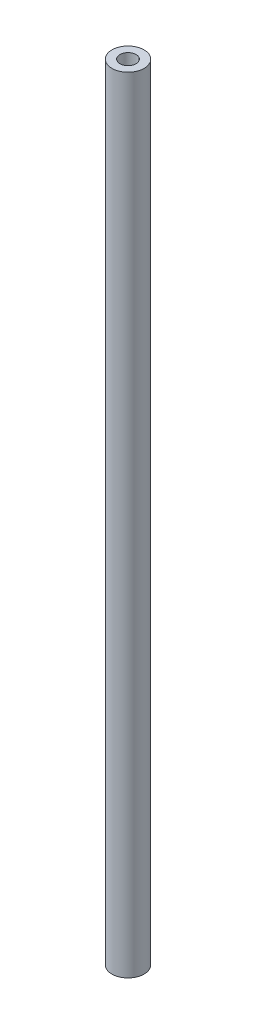
SolidWorks part; units mm, degrees
material "PEI"
ref_plane "Спереди" through (0, 0, 0) normal (0, 0, 1) x (1, 0, 0)
ref_plane "Сверху" through (0, 0, 0) normal (0, 1, 0) x (1, 0, 0)
ref_plane "Справа" through (0, 0, 0) normal (1, 0, 0) x (0, 0, -1)
sketch "Эскиз1" plane through (0, 0, 0) normal (0, 1, 0) x (1, 0, 0)
  circle A0 centre (0, 0) radius 10
  circle A1 centre (0, 0) radius 5
  dimension "D1" = 20
  dimension "D2" = 10
extrude "Бобышка-Вытянуть1" add sketch "Эскиз1" along normal blind 488
